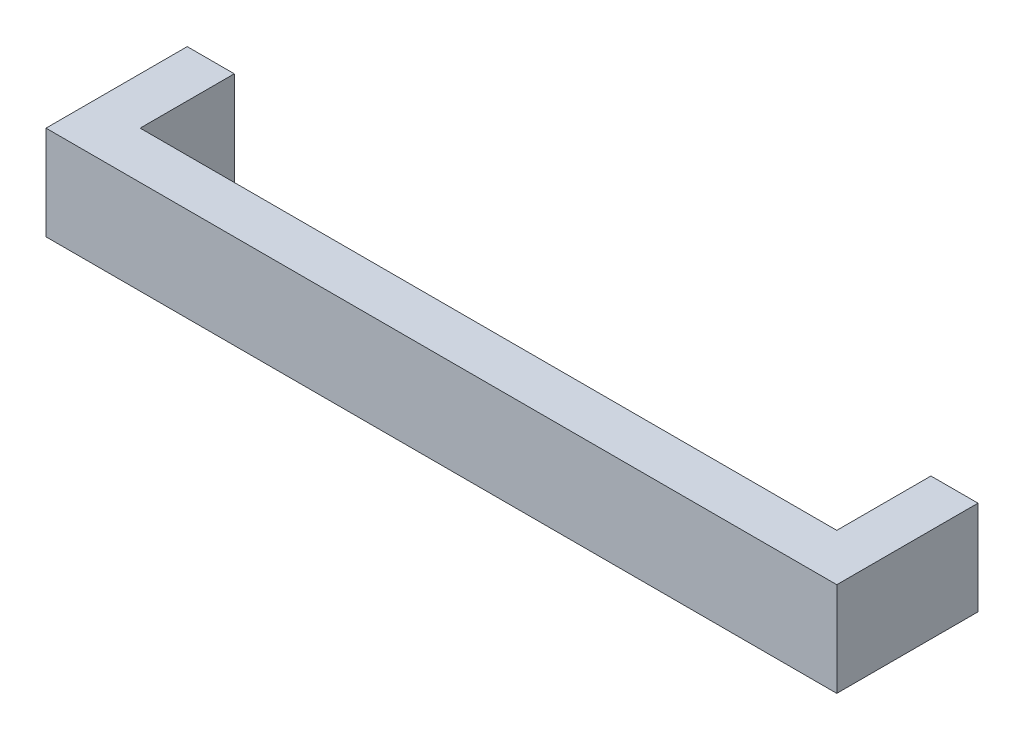
SolidWorks part; units mm, degrees
ref_plane "Front Plane" through (0, 0, 0) normal (0, 0, 1) x (1, 0, 0)
ref_plane "Top Plane" through (0, 0, 0) normal (0, 1, 0) x (1, 0, 0)
ref_plane "Right Plane" through (0, 0, 0) normal (1, 0, 0) x (0, 0, -1)
sketch "Sketch1" plane through (0, 0, 0) normal (0, 1, 0) x (1, 0, 0)
  line L0 (0, 0) -> (74, 0)
  line L1 (74, 0) -> (74, 10)
  line L2 (0, 0) -> (0, 10)
  dimension "D2" = 10
  dimension "D1" = 74
  dimension "D3" = 10
extrude "Extrude-Thin1" add sketch "Sketch1" along normal blind 10 thin
